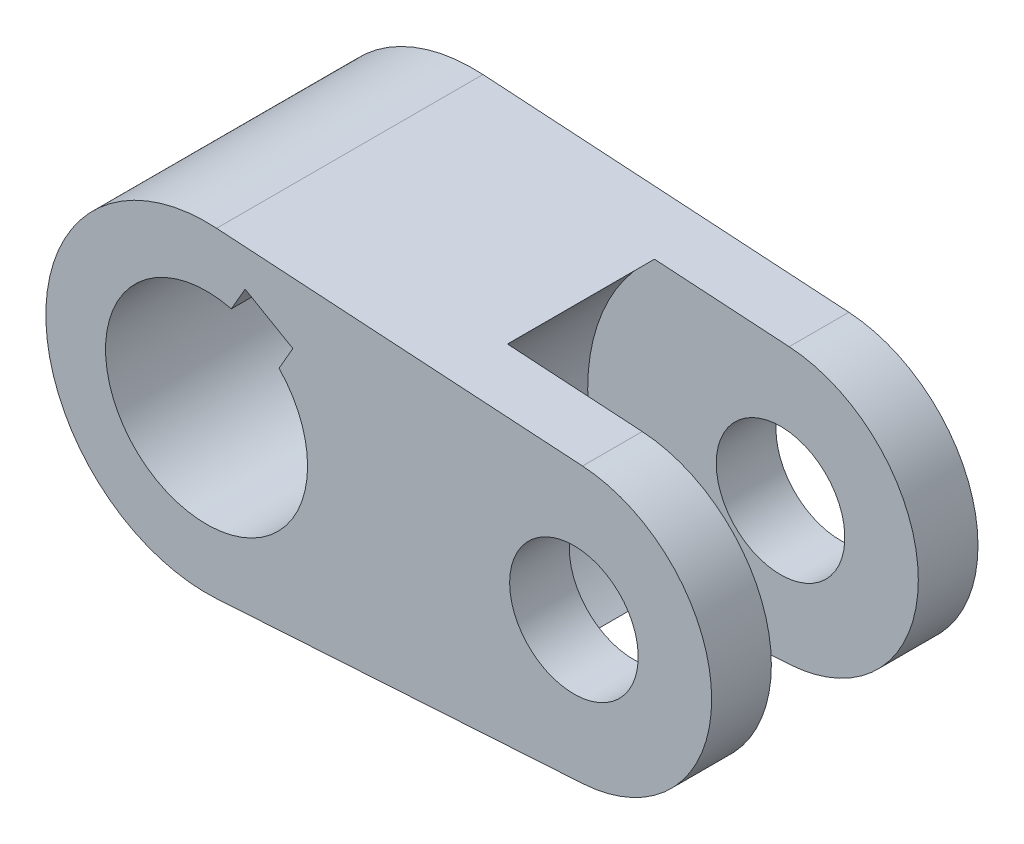
SolidWorks part; units mm, degrees
ref_plane "Спереди" through (0, 0, 0) normal (0, 0, 1) x (1, 0, 0)
ref_plane "Сверху" through (0, 0, 0) normal (0, 1, 0) x (1, 0, 0)
ref_plane "Справа" through (0, 0, 0) normal (1, 0, 0) x (0, 0, -1)
sketch "Эскиз1" plane through (0, 0, 0) normal (0, 0, 1) x (1, 0, 0)
  line L0 (0, 0) -> (40, 0) construction
  line L1 (40.9375, 14.9707) -> (1.0938, 17.4658)
  line L2 (40.9375, -14.9707) -> (1.0938, -17.4658)
  line L3 (0, 0) -> (6.8, 11.7779) construction
  line L4 (2.6934, 10.6652) -> (4.2019, 13.2779)
  line L5 (4.2019, 13.2779) -> (9.3981, 10.2779)
  line L6 (9.3981, 10.2779) -> (7.8896, 7.6652)
  arc A0 (1.0938, 17.4658) -> (1.0938, -17.4658) centre (0, 0) ccw
  arc A1 (40.9375, -14.9707) -> (40.9375, 14.9707) centre (40, 0) ccw
  arc A2 (2.6934, 10.6652) -> (7.8896, 7.6652) centre (0, 0) ccw
  circle A3 centre (40, 0) radius 7
  point P15 (6.8, 11.7779)
  dimension "D1" = 17.5
  dimension "D2" = 15
  dimension "D5" = 22
  dimension "D8" = 14
  dimension "D3" = 40
  dimension "D4" = 24.6
  dimension "D6" = 6
  dimension "D7" = 60
extrude "Бобышка-Вытянуть1" add sketch "Эскиз1" along normal mid plane 29
sketch "Эскиз2" plane through (0, 0, 0) normal (0, 0, 1) x (1, 0, 0)
  circle A0 centre (40, 0) radius 21
  dimension "D1" = 42
extrude "Вырез-Вытянуть1" cut sketch "Эскиз2" against normal mid plane 16
